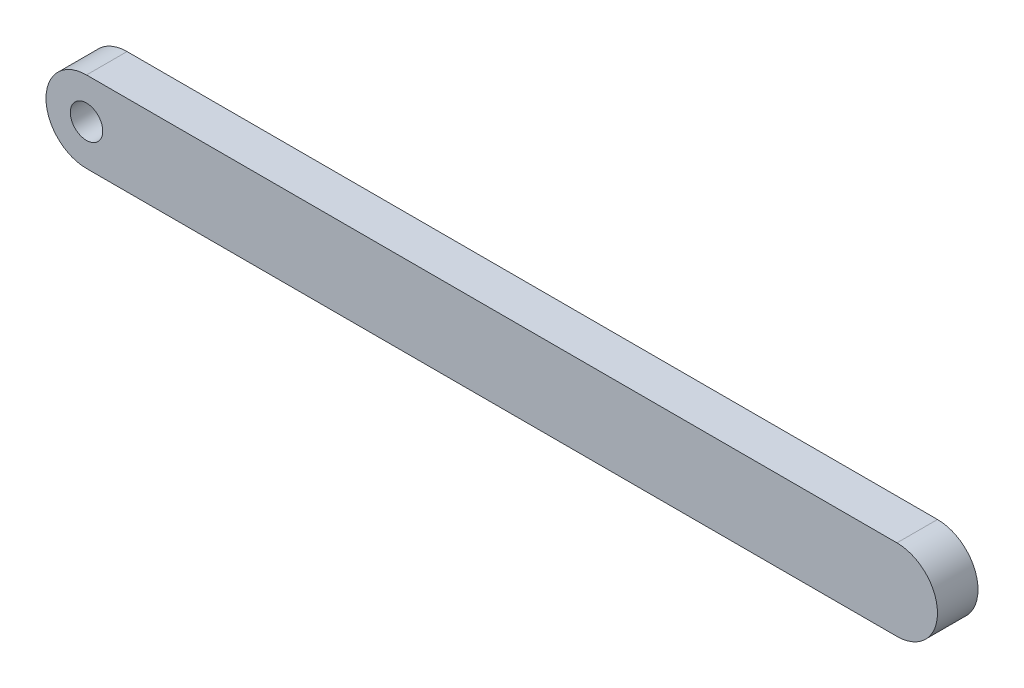
SolidWorks part; units mm, degrees
material "6061 Alloy"
ref_plane "Front Plane" through (0, 0, 0) normal (0, 0, 1) x (1, 0, 0)
ref_plane "Top Plane" through (0, 0, 0) normal (0, 1, 0) x (1, 0, 0)
ref_plane "Right Plane" through (0, 0, 0) normal (1, 0, 0) x (0, 0, -1)
sketch "Sketch1" plane through (0, 0, 0) normal (0, 0, 1) x (1, 0, 0)
  line L1 (0, 0) -> (100, 0)
  line L2 (0, 0) -> (0, -10)
  line L3 (0, -10) -> (100, -10)
  line L4 (100, 0) -> (100, -10)
  arc A0 (100, 0) -> (100, -10) centre (100, -5) cw
  arc A1 (0, 0) -> (0, -10) centre (0, -5) ccw
  dimension "D1" = 100
  dimension "D2" = 10
extrude "Boss-Extrude1" add sketch "Sketch1" along normal blind 5 contours L2 A1 | L4 L1 L2 L3 | A0 L4
sketch "Sketch2" plane through (0, 0, 5) normal (0, 0, 1) x (1, 0, 0)
  circle A0 centre (0, -5) radius 2
  dimension "D1" = 4
extrude "Cut-Extrude1" cut sketch "Sketch2" against normal through all
